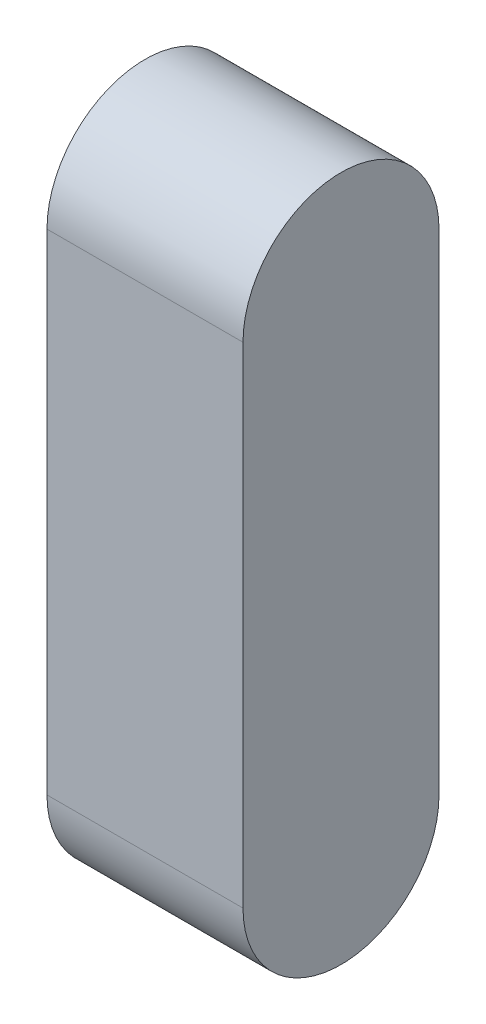
SolidWorks part; units mm, degrees
ref_plane "Front Plane" through (0, 0, 0) normal (1, 0, 0) x (0, 1, 0)
ref_plane "Top Plane" through (0, 0, 0) normal (0, 0, 1) x (0, 1, 0)
ref_plane "Right Plane" through (0, 0, 0) normal (0, 1, 0) x (-1, 0, 0)
sketch "Sketch1" plane through (0, 0, 0) normal (1, 0, 0) x (0, 1, 0)
  line L0 (-5, 0) -> (5, 0) construction
  line L1 (-5, 2) -> (5, 2)
  line L2 (-5, -2) -> (5, -2)
  arc A0 (-5, 2) -> (-5, -2) centre (-5, 0) ccw
  arc A1 (5, -2) -> (5, 2) centre (5, 0) ccw
  point P2 (0, 0)
  dimension "D2" = 2
  dimension "D1" = 10
extrude "Boss-Extrude1" add sketch "Sketch1" along normal mid plane 4
